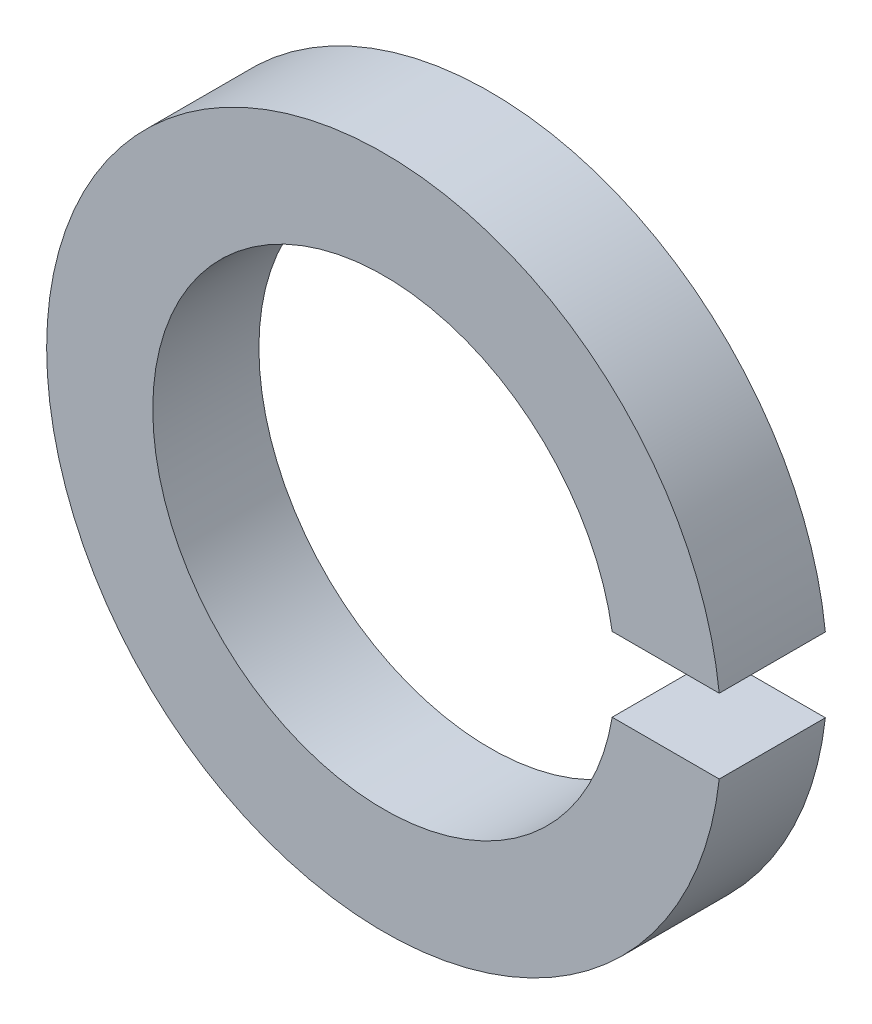
SolidWorks part; units mm, degrees
ref_plane "Спереди" through (0, 0, 0) normal (0, 0, 1) x (1, 0, 0)
ref_plane "Сверху" through (0, 0, 0) normal (0, 1, 0) x (1, 0, 0)
ref_plane "Справа" through (0, 0, 0) normal (1, 0, 0) x (0, 0, -1)
sketch "Эскиз1" plane through (0, 0, 0) normal (0, 0, 1) x (1, 0, 0)
  circle A0 centre (0, 0) radius 4.45
  circle A1 centre (0, 0) radius 3.05
  dimension "D1" = 8.9
  dimension "D2" = 6.1
extrude "Вытянуть1" add sketch "Эскиз1" along normal blind 1.4
sketch "Эскиз2" plane through (0, 0, 1.4) normal (0, 0, 1) x (1, 0, 0)
  line L0 (0, 0) -> (0.123, 0) construction
  line L1 (4.45, 0) -> (-4.45, 0) construction
  line L3 (2.9955, 0.49) -> (4.5243, 0.49)
  line L4 (2.9955, 0.49) -> (2.9955, -0.49)
  line L5 (2.9955, -0.49) -> (4.5243, -0.49)
  line L6 (4.5243, 0.49) -> (4.5243, -0.49)
  circle A0 centre (0, 0) radius 4.45 construction
  dimension "D1" = 0.49
  dimension "D2" = 0.98
extrude "Вырез-Вытянуть1" cut sketch "Эскиз2" against normal through all
